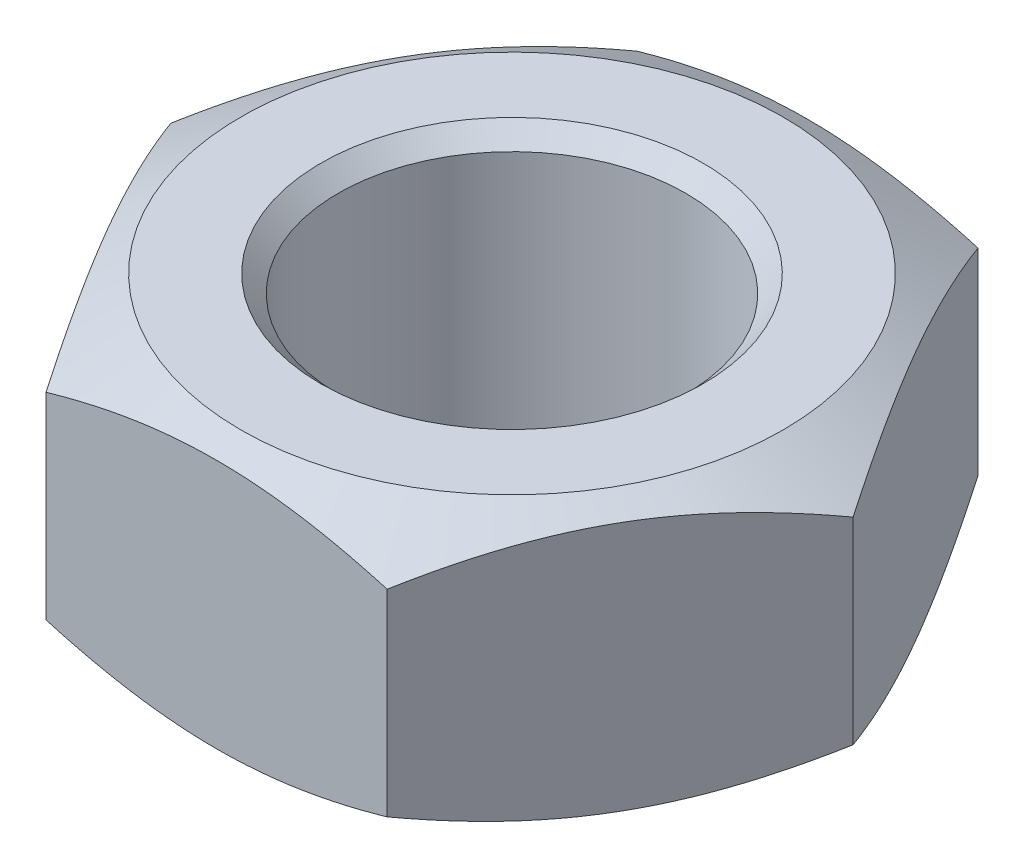
SolidWorks part; units mm, degrees
ref_plane "Спереди" through (0, 0, 0) normal (0, 0, 1) x (1, 0, 0)
ref_plane "Сверху" through (0, 0, 0) normal (0, 1, 0) x (1, 0, 0)
ref_plane "Справа" through (0, 0, 0) normal (1, 0, 0) x (0, 0, -1)
sketch "Эскиз1" plane through (0, 0, 0) normal (0, 1, 0) x (1, 0, 0)
  line L0 (-4.9075, 8.5) -> (4.9075, 8.5)
  line L1 (4.9075, 8.5) -> (9.815, 0)
  line L2 (9.815, 0) -> (4.9075, -8.5)
  line L3 (4.9075, -8.5) -> (-4.9075, -8.5)
  line L4 (-4.9075, -8.5) -> (-9.815, 0)
  line L5 (-9.815, 0) -> (-4.9075, 8.5)
  dimension "D5" = 8.5
  dimension "D2" = 120
  dimension "D3" = 120
  dimension "D4" = 120
  dimension "D6" = 8.5
  dimension "D7" = 8.5
  dimension "D8" = 8.5
  dimension "D9" = 8.5
  dimension "D10" = 120
  dimension "D11" = 8.5
extrude "Вытянуть1" add sketch "Эскиз1" against normal blind 8
sketch "Эскиз5" plane through (0, -8, 0) normal (0, -1, 0) x (1, 0, 0)
  circle A0 centre (0, 0) radius 5
  dimension "D1" = 10
extrude "Вырез-Вытянуть1" cut sketch "Эскиз5" against normal through all
ref_axis "Ось1" through (0, 0, 0) along (0, -1, 0)
ref_plane "Плоскость1" through (0, 0, 0) normal (0, 0, 1) x (1, 0, 0)
sketch "Эскиз4" plane through (0, 0, 0) normal (0, 0, 1) x (1, 0, 0)
  line L0 (-9.815, -1.1633) -> (-7.8, 0)
  line L1 (-9.815, -8) -> (-9.815, 0) construction
  line L2 (-9.815, 0) -> (-4.9075, 0) construction
  line L3 (-7.8, 0) -> (-9.815, 0)
  line L4 (-9.815, 0) -> (-9.815, -1.1633)
  line L5 (-9.815, -6.8367) -> (-7.8, -8)
  line L6 (-9.815, -8) -> (-4.9075, -8) construction
  line L7 (-7.8, -8) -> (-9.815, -8)
  line L8 (-9.815, -8) -> (-9.815, -6.8367)
  line L9 (0, 0) -> (0, -8) construction
  dimension "D1" = 7.8
  dimension "D2" = 30
  dimension "D3" = 7.8
  dimension "D4" = 30
revolve "Вырез-Повернуть1" cut sketch "Эскиз4" angle 360 about axis through (0, 0, 0) along (0, -1, 0)
chamfer "Фаска1" distance 0.5 angle 45 2 edges at (0, -8, -5) (0, 0, -5)
